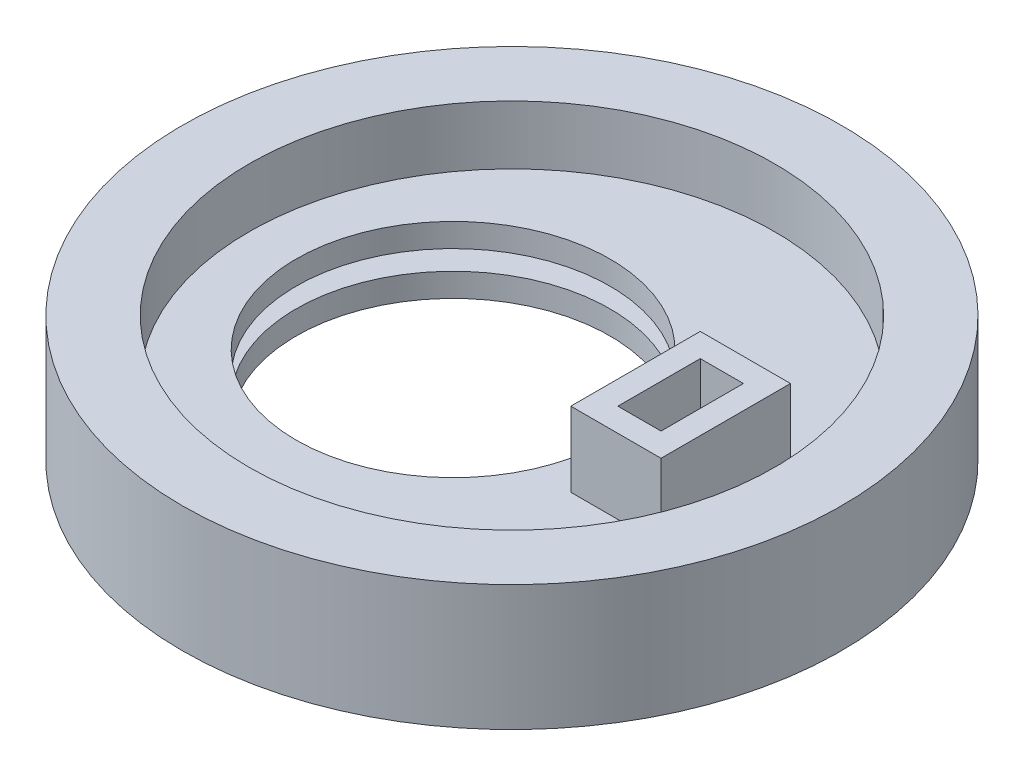
SolidWorks part; units mm, degrees
ref_plane "Front Plane" through (0, 0, 0) normal (0, 0, 1) x (1, 0, 0)
ref_plane "Top Plane" through (0, 0, 0) normal (0, 1, 0) x (1, 0, 0)
ref_plane "Right Plane" through (0, 0, 0) normal (1, 0, 0) x (0, 0, -1)
sketch "Sketch1" plane through (0, 0, 0) normal (0, 1, 0) x (1, 0, 0)
  circle A0 centre (0, 0) radius 14.6
  dimension "D1" = 29.2
extrude "Boss-Extrude1" add sketch "Sketch1" along normal blind 3
shell "Shell2" thickness 1
sketch "Sketch2" plane through (0, 0, 0) normal (0, 1, 0) x (1, 0, 0)
  line L0 (14.6, 0) -> (-19.6615, 0) construction
  line L1 (0, 0) -> (0, -24.1396) construction
  line L3 (9.7, 2.1) -> (7.5, 2.1)
  line L4 (9.7, 2.1) -> (9.7, -2.1)
  line L5 (9.7, -2.1) -> (7.5, -2.1)
  line L6 (7.5, 2.1) -> (7.5, -2.1)
  circle A0 centre (0, 0) radius 14.6 construction
  dimension "D1" = 4.2
  dimension "D2" = 2.2
  dimension "D3" = 2.1
  dimension "D4" = 7.5
extrude "Boss-Extrude2" add sketch "Sketch2" along normal blind 5
shell "Shell3" thickness 1.2
sketch "Sketch3" plane through (0, 1.2, 0) normal (0, 1, 0) x (1, 0, 0)
  circle A0 centre (-3, 0) radius 8
  circle A1 centre (0, 0) radius 13.4 construction
  dimension "D1" = 16
  dimension "D2" = 3
extrude "Cut-Extrude1" cut sketch "Sketch3" against normal through all
